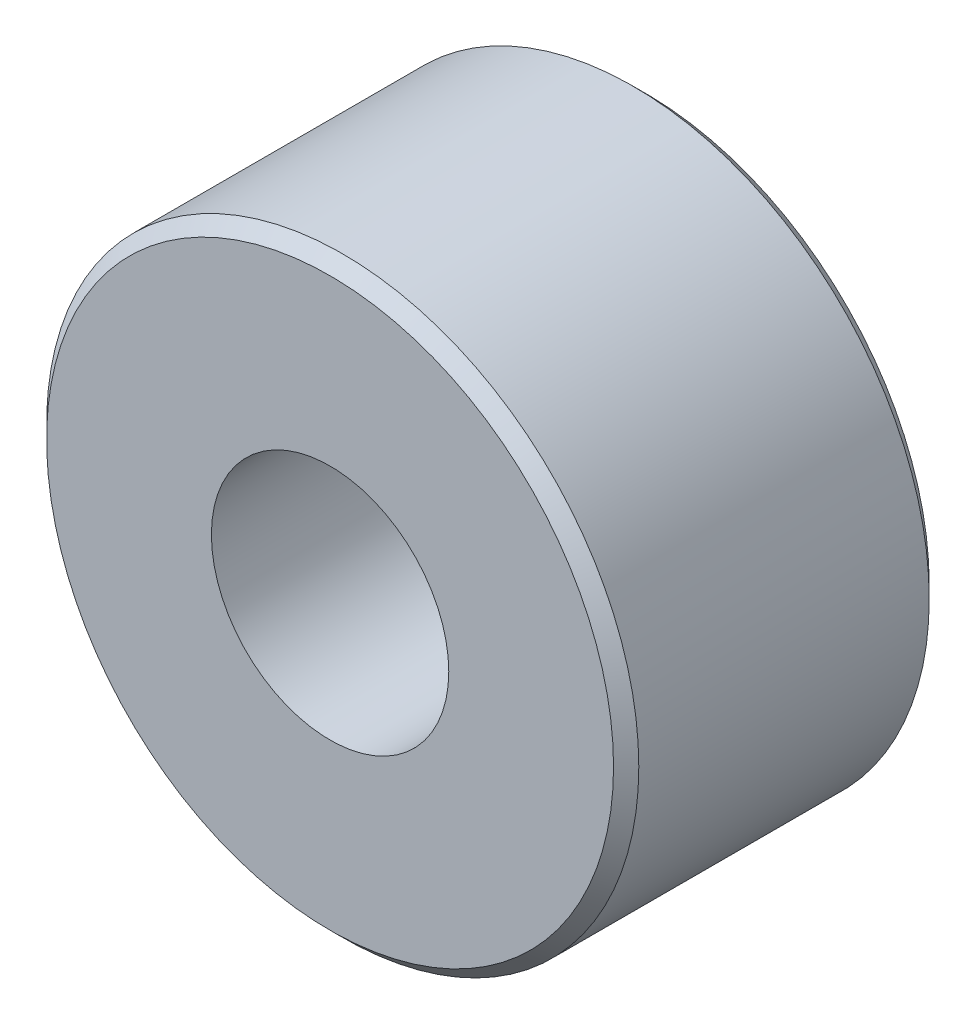
SolidWorks part; units mm, degrees
material "AISI 304"
ref_plane "Front Plane" through (0, 0, 0) normal (0, 0, 1) x (1, 0, 0)
ref_plane "Top Plane" through (0, 0, 0) normal (0, 1, 0) x (1, 0, 0)
ref_plane "Right Plane" through (0, 0, 0) normal (1, 0, 0) x (0, 0, -1)
sketch "Sketch1" plane through (0, 0, 0) normal (0, 0, 1) x (1, 0, 0)
  circle A0 centre (0, 0) radius 5.9563
  dimension "D1" = 11.9126
extrude "Extrude1" add sketch "Sketch1" along normal mid plane 6.35
sketch "Sketch2" plane through (0, 0, 3.175) normal (0, 0, 1) x (1, 0, 0)
  circle A0 centre (0, 0) radius 2.3876
  dimension "D1" = 4.7752
extrude "Extrude2" cut sketch "Sketch2" against normal through all
chamfer "Chamfer1" distance 0.254 angle 45 2 edges at (5.9563, 0, -3.175) (5.9563, 0, 3.175)
